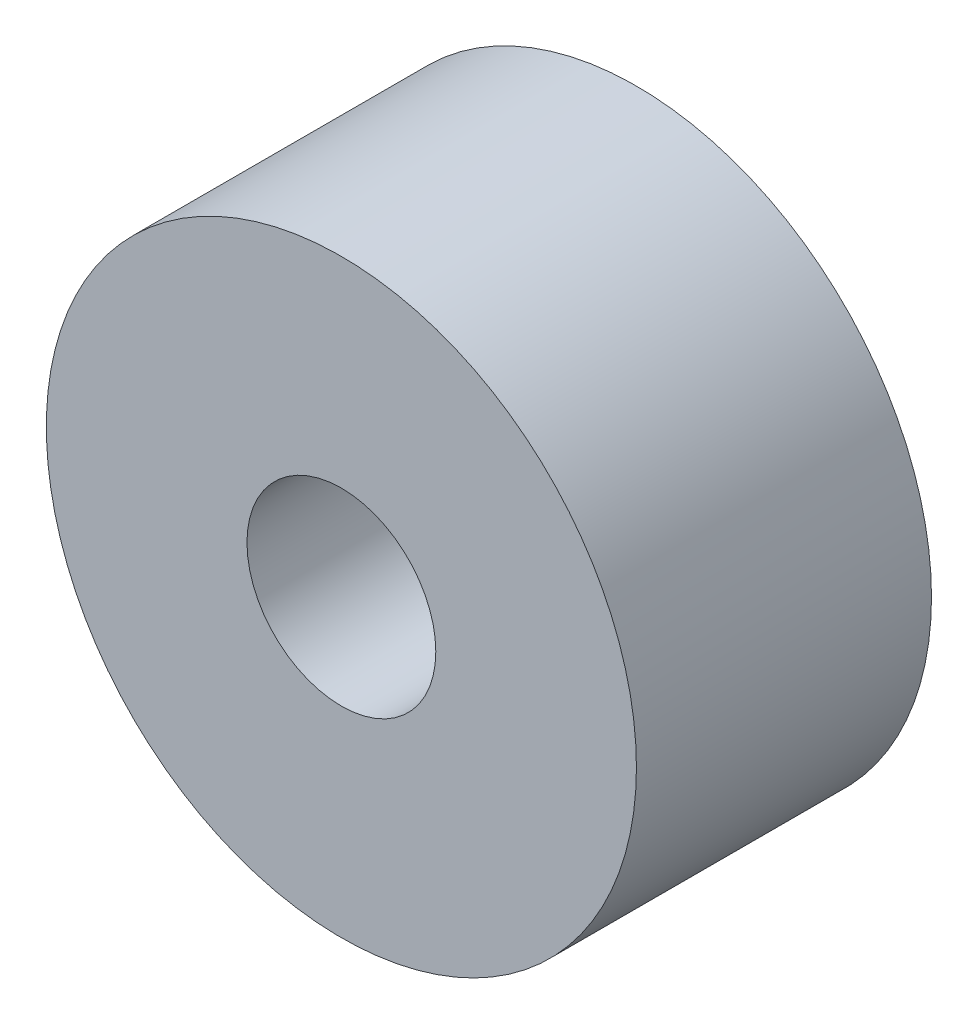
SolidWorks part; units mm, degrees
ref_plane "Front Plane" through (0, 0, 0) normal (0, 0, 1) x (1, 0, 0)
ref_plane "Top Plane" through (0, 0, 0) normal (0, 1, 0) x (1, 0, 0)
ref_plane "Right Plane" through (0, 0, 0) normal (1, 0, 0) x (0, 0, -1)
sketch "Sketch2" plane through (0, 0, 0) normal (0, 0, 1) x (1, 0, 0)
  circle A0 centre (0, 0) radius 5
  circle A1 centre (0, 0) radius 1.6
  dimension "D1" = 10
  dimension "D2" = 3.2
extrude "Boss-Extrude1" add sketch "Sketch2" along normal blind 5
